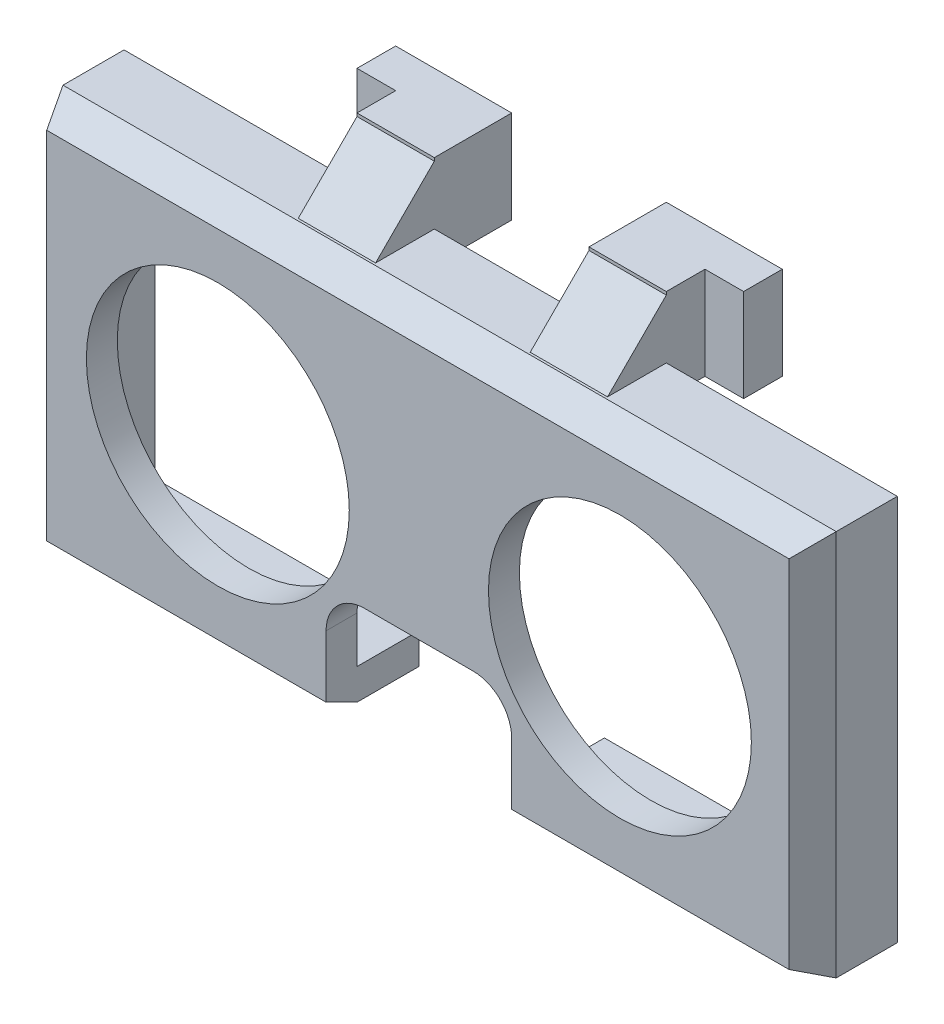
SolidWorks part; units mm, degrees
ref_plane "Front Plane" through (0, 0, 0) normal (0, 0, 1) x (1, 0, 0)
ref_plane "Top Plane" through (0, 0, 0) normal (0, 1, 0) x (1, 0, 0)
ref_plane "Right Plane" through (0, 0, 0) normal (1, 0, 0) x (0, 0, -1)
sketch "Sketch1" plane through (0, 0, 0) normal (0, 0, 1) x (1, 0, 0)
  line L0 (-3.5, -10) -> (3.5, -10)
  line L1 (3.5, -5) -> (-3.5, -5)
  line L2 (-6, -7.5) -> (-6, -10)
  line L3 (6, -7.5) -> (6, -10)
  line L4 (-23.0644, 10.5) -> (-23.0644, -10.5)
  line L5 (-23.0644, -10.5) -> (22.9356, -10.5)
  line L6 (22.9356, -10.5) -> (22.9356, 10.5)
  line L7 (22.9356, 10.5) -> (-23.0644, 10.5)
  line L8 (-25.0644, 12.5) -> (-25.0644, -12.5)
  line L9 (-25.0644, -12.5) -> (24.9356, -12.5)
  line L10 (24.9356, -12.5) -> (24.9356, 12.5)
  line L11 (24.9356, 12.5) -> (-25.0644, 12.5)
  line L12 (-22.5644, 10) -> (-22.5644, -10)
  line L13 (-22.5644, -10) -> (22.4356, -10)
  line L14 (22.4356, -10) -> (22.4356, 10)
  line L15 (22.4356, 10) -> (-22.5644, 10)
  line L16 (-6, -10) -> (-6, -10.5)
  line L17 (6, -10) -> (6, -10.5)
  line L18 (-3.5, -9) -> (3.5, -9)
  line L19 (3.5, -6) -> (-3.5, -6)
  arc A0 (3.5, -10) -> (3.5, -5) centre (3.5, -7.5) ccw
  arc A1 (-3.5, -5) -> (-3.5, -10) centre (-3.5, -7.5) ccw
  circle A3 centre (-13, 0) radius 8.5
  circle A6 centre (13, 0) radius 8.5
  arc A12 (3.5, -9) -> (3.5, -6) centre (3.5, -7.5) ccw
  arc A13 (-3.5, -6) -> (-3.5, -9) centre (-3.5, -7.5) ccw
  dimension "D4" = 17
  dimension "D5" = 17
  dimension "D1" = 1
  dimension "D2" = 0.5
  dimension "D3" = 2.5
extrude "Boss-Extrude1" add sketch "Sketch1" along normal blind 2 contours A1 L1 A0 L3 L13 L14 L15 L12 L2 A6 A3 | L13 L17 L5 L6 L7 L4 L16 L12 L15 L14
sketch "Sketch2" plane through (0, 0, 0) normal (0, 0, -1) x (-1, 0, 0)
  line L8 (25.0644, -12.5) -> (25.0644, 12.5)
  line L9 (-24.9356, -12.5) -> (25.0644, -12.5)
  line L10 (-24.9356, 12.5) -> (-24.9356, -12.5)
  line L11 (25.0644, 12.5) -> (-24.9356, 12.5)
  line L12 (25.0644, -12.5) -> (25.0644, 12.5)
  line L13 (-24.9356, -12.5) -> (25.0644, -12.5)
  line L14 (-24.9356, 12.5) -> (-24.9356, -12.5)
  line L15 (25.0644, 12.5) -> (-24.9356, 12.5)
  line L16 (-6, -10.5) -> (-6, -12.5)
  line L17 (6, -10.5) -> (6, -12.5)
  line L20 (23.0644, -10.5) -> (23.0644, 10.5)
  line L21 (-22.9356, -10.5) -> (23.0644, -10.5)
  line L22 (-22.9356, 10.5) -> (-22.9356, -10.5)
  line L23 (23.0644, 10.5) -> (-22.9356, 10.5)
  line L24 (23.0644, -10.5) -> (23.0644, 10.5)
  line L25 (-22.9356, -10.5) -> (23.0644, -10.5)
  line L26 (-22.9356, 10.5) -> (-22.9356, -10.5)
  line L27 (23.0644, 10.5) -> (-22.9356, 10.5)
  line M13 (6, -10.5) -> (23.0644, -10.5)
  line M14 (23.0644, -10.5) -> (23.0644, 10.5)
  line M15 (23.0644, 10.5) -> (-22.9356, 10.5)
  line M16 (-22.9356, 10.5) -> (-22.9356, -10.5)
  line M17 (-22.9356, -10.5) -> (-6, -10.5)
  dimension "D1" = 0
  dimension "D2" = 0
extrude "Boss-Extrude2" add sketch "Sketch2" along normal blind 4 and the other way up to surface (2 mm away) contours L17 L13 L12 L15 L14 L16 M13 M17 M16 M15 M14 other way up to face at (21.5, 0, 2)
chamfer "Chamfer1" distance 1 angle 64 5 edges at (-15.5322, -12.5, 2) (-25.0644, 0, 2) (15.4678, -12.5, 2) (24.9356, 0, 2) (-0.0644, 12.5, 2)
sketch "Sketch3" plane through (0, 0, 0) normal (0, 0, -1) x (-1, 0, 0)
  line L0 (-5, 8.75) -> (5, 8.75) construction
  line L1 (-5, 9.95) -> (5, 9.95)
  line L2 (-5, 7.55) -> (5, 7.55)
  line L3 (-22.9356, 10.5) -> (23.0644, 10.5) construction
  arc A0 (-5, 9.95) -> (-5, 7.55) centre (-5, 8.75) ccw
  arc A1 (5, 7.55) -> (5, 9.95) centre (5, 8.75) ccw
  point P2 (0, 8.75)
  dimension "D2" = 1.2
  dimension "D1" = 0
  dimension "D3" = 1.75
  dimension "D4" = 10
extrude "Cut-Extrude1" cut sketch "Sketch3" against normal blind 1
sketch "Sketch5" plane through (0, 10.5, 0) normal (0, -1, 0) x (1, 0, 0)
  line L0 (-23.0644, -4) -> (22.9356, -4) construction
  line L1 (5, -4) -> (10, -4)
  line L2 (5, -4) -> (5, -6.5)
  line L3 (5, -6.5) -> (10, -6.5)
  line L4 (10, -4) -> (10, -6.5)
  line L6 (-5, -4) -> (-10, -4)
  line L7 (-5, -4) -> (-5, -6.5)
  line L8 (-5, -6.5) -> (-10, -6.5)
  line L9 (-10, -4) -> (-10, -6.5)
  line L10 (-5, -6.5) -> (-12.5, -6.5)
  line L11 (-5, -6.5) -> (-5, -9)
  line L12 (-5, -9) -> (-12.5, -9)
  line L13 (-12.5, -6.5) -> (-12.5, -9)
  line L14 (5, -6.5) -> (12.5, -6.5)
  line L15 (5, -6.5) -> (5, -9)
  line L16 (5, -9) -> (12.5, -9)
  line L17 (12.5, -6.5) -> (12.5, -9)
  line M14 (-23.0644, -4) -> (22.9356, -4)
  dimension "D1" = 10
  dimension "D2" = 5
  dimension "D3" = 2.5
  dimension "D4" = 2.5
  dimension "D5" = 5
  dimension "D6" = 5
  dimension "D7" = 2.5
  dimension "D8" = 7.5
  dimension "D9" = 7.5
  dimension "D10" = 2.5
extrude "Boss-Extrude3" add sketch "Sketch5" against normal offset from surface (6 mm away) 4 contours L4 L2 L3 M14 | L17 L14 L3 L15 L16 | L9 L8 L7 M14 | L10 L13 L12 L11 L8 up to face at (-0.0644, 12.5, -2.0252) offset beyond the face yes
chamfer "Chamfer2" distance 3.8 angle 45 2 edges at (7.5, 12.5, -4) (-7.5, 12.5, -4)
